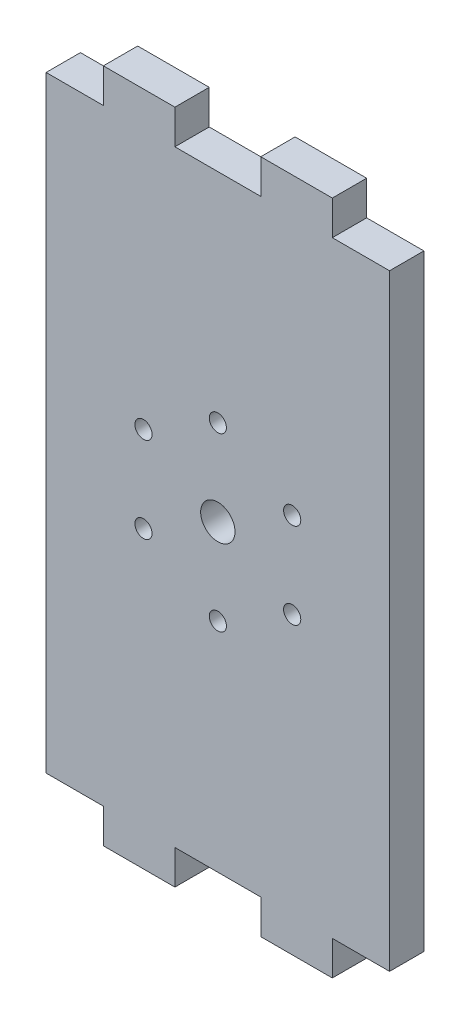
SolidWorks part; units mm, degrees
ref_plane "Alzado" through (0, 0, 0) normal (0, 0, 1) x (1, 0, 0)
ref_plane "Planta" through (0, 0, 0) normal (0, 1, 0) x (1, 0, 0)
ref_plane "Vista lateral" through (0, 0, 0) normal (1, 0, 0) x (0, 0, -1)
sketch "Sketch1" plane through (0, 0, 0) normal (0, 0, 1) x (1, 0, 0)
  line L0 (-15, 26.5) -> (-10, 26.5)
  line L1 (-10, 29.5) -> (-3.75, 29.5)
  line L2 (-15, 26.5) -> (-15, -26.5)
  line L3 (-10, -29.5) -> (-3.75, -29.5)
  line L4 (15, 26.5) -> (15, -26.5)
  line L5 (-15, 29.5) -> (15, -29.5) construction
  line L6 (-15, -29.5) -> (15, 29.5) construction
  line L7 (-10, 26.5) -> (-10, 29.5)
  line L8 (-3.75, 29.5) -> (-3.75, 26.5)
  line L9 (-3.75, 26.5) -> (3.75, 26.5)
  line L10 (3.75, 26.5) -> (3.75, 29.5)
  line L11 (10, 29.5) -> (10, 26.5)
  line L12 (10, 26.5) -> (15, 26.5)
  line L13 (-15, 0) -> (15, 0) construction
  line L14 (0, 26.5) -> (0, 0) construction
  line L15 (10, -26.5) -> (15, -26.5)
  line L16 (10, -29.5) -> (10, -26.5)
  line L17 (-3.75, -29.5) -> (-3.75, -26.5)
  line L18 (3.75, -26.5) -> (3.75, -29.5)
  line L19 (-3.75, -26.5) -> (3.75, -26.5)
  line L20 (-10, -26.5) -> (-10, -29.5)
  line L21 (-15, -26.5) -> (-10, -26.5)
  line L22 (3.75, 29.5) -> (10, 29.5)
  line L23 (3.75, -29.5) -> (10, -29.5)
  line L24 (-15, 26.5) -> (-15, 29.5) construction
  line L25 (-15, 29.5) -> (-10, 29.5) construction
  line L26 (15, 26.5) -> (15, 29.5) construction
  line L27 (15, 29.5) -> (10, 29.5) construction
  line L28 (-15, -26.5) -> (-15, -29.5) construction
  line L29 (-15, -29.5) -> (-10, -29.5) construction
  line L30 (15, -26.5) -> (15, -29.5) construction
  line L31 (15, -29.5) -> (10, -29.5) construction
  line L32 (-6.4952, 3.75) -> (6.4952, -3.75) construction
  line L33 (6.4952, 3.75) -> (-6.4952, -3.75) construction
  line L34 (0, 0) -> (0, -7.5) construction
  circle A0 centre (0, 0) radius 7.5 construction
  circle A1 centre (0, 7.5) radius 0.75
  circle A2 centre (6.4952, 3.75) radius 0.75
  circle A3 centre (6.4952, -3.75) radius 0.75
  circle A4 centre (0, -7.5) radius 0.75
  circle A5 centre (-6.4952, -3.75) radius 0.75
  circle A6 centre (-6.4952, 3.75) radius 0.75
  circle A7 centre (0, 0) radius 1.5
  point P0 (0, 0)
  point P45 (0, 0)
  dimension "D7" = 3
  dimension "D8" = 15
  dimension "D9" = 1.5
  dimension "D1" = 59
  dimension "D2" = 30
  dimension "D3" = 3
  dimension "D4" = 5
  dimension "D5" = 5
  dimension "D6" = 7.5
  dimension "D10" = 60
  dimension "D11" = 60
  dimension "D12" = 60
extrude "Boss-Extrude1" add sketch "Sketch1" along normal blind 3
